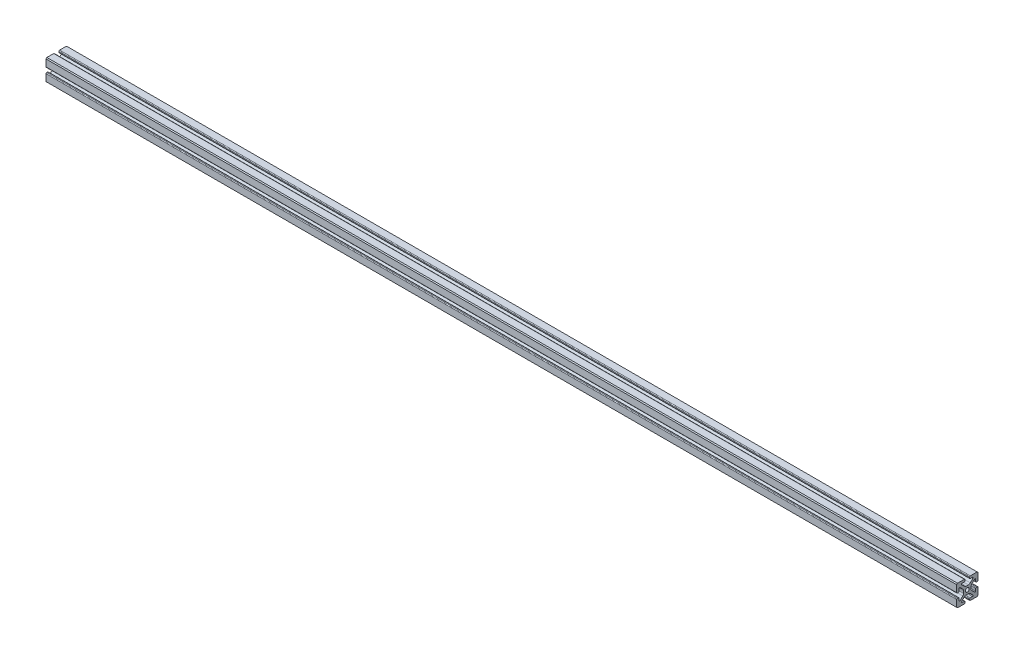
SolidWorks part; units mm, degrees
ref_plane "Front Plane" through (0, 0, 0) normal (0, 0, 1) x (1, 0, 0)
ref_plane "Top Plane" through (0, 0, 0) normal (0, 1, 0) x (1, 0, 0)
ref_plane "Right Plane" through (0, 0, 0) normal (1, 0, 0) x (0, 0, -1)
ref_plane "Plane1" through (0, 0, 0) normal (-1, 0, 0) x (0, -1, 0)
sketch "Sketch1" plane through (0, 0, 0) normal (-1, 0, 0) x (0, -1, 0)
  line L0 (19.05, 5.334) -> (19.05, 17.526)
  line L1 (19.05, 17.526) -> (17.526, 19.05)
  line L2 (17.526, 19.05) -> (5.334, 19.05)
  line L3 (4.064, 17.78) -> (4.064, 16.1266)
  line L4 (5.334, 14.8566) -> (9.0964, 14.8566)
  line L5 (10.287, 13.666) -> (10.287, 13.6538)
  line L6 (9.9383, 12.8119) -> (5.2776, 8.1513)
  line L7 (1.91, 6.7564) -> (-1.91, 6.7564)
  line L8 (-5.2776, 8.1513) -> (-9.9383, 12.8119)
  line L9 (-10.287, 13.6538) -> (-10.287, 13.666)
  line L10 (-9.0964, 14.8566) -> (-5.334, 14.8566)
  line L11 (-4.064, 16.1266) -> (-4.064, 17.78)
  line L12 (-5.334, 19.05) -> (-17.526, 19.05)
  line L13 (-17.526, 19.05) -> (-19.05, 17.526)
  line L14 (-19.05, 17.526) -> (-19.05, 5.334)
  line L15 (-17.78, 4.064) -> (-16.1266, 4.064)
  line L16 (-14.8566, 5.334) -> (-14.8566, 9.0964)
  line L17 (-13.666, 10.287) -> (-13.6538, 10.287)
  line L18 (-12.8119, 9.9383) -> (-8.1513, 5.2776)
  line L19 (-6.7564, 1.91) -> (-6.7564, -1.91)
  line L20 (-8.1513, -5.2776) -> (-12.8119, -9.9383)
  line L21 (-13.6538, -10.287) -> (-13.666, -10.287)
  line L22 (-14.8566, -9.0964) -> (-14.8566, -5.334)
  line L23 (-16.1266, -4.064) -> (-17.78, -4.064)
  line L24 (-19.05, -5.334) -> (-19.05, -17.526)
  line L25 (-19.05, -17.526) -> (-17.526, -19.05)
  line L26 (-17.526, -19.05) -> (-5.334, -19.05)
  line L27 (-4.064, -17.78) -> (-4.064, -16.1266)
  line L28 (-5.334, -14.8566) -> (-9.0964, -14.8566)
  line L29 (-10.287, -13.666) -> (-10.287, -13.6538)
  line L30 (-9.9383, -12.8119) -> (-5.2776, -8.1513)
  line L31 (-1.91, -6.7564) -> (1.91, -6.7564)
  line L32 (5.2776, -8.1513) -> (9.9383, -12.8119)
  line L33 (10.287, -13.6538) -> (10.287, -13.666)
  line L34 (9.0964, -14.8566) -> (5.334, -14.8566)
  line L35 (4.064, -16.1266) -> (4.064, -17.78)
  line L36 (5.334, -19.05) -> (17.526, -19.05)
  line L37 (17.526, -19.05) -> (19.05, -17.526)
  line L38 (19.05, -17.526) -> (19.05, -5.334)
  line L39 (17.78, -4.064) -> (16.1266, -4.064)
  line L40 (14.8566, -5.334) -> (14.8566, -9.0964)
  line L41 (13.666, -10.287) -> (13.6538, -10.287)
  line L42 (12.8119, -9.9383) -> (8.1513, -5.2776)
  line L43 (6.7564, -1.91) -> (6.7564, 1.91)
  line L44 (8.1513, 5.2776) -> (12.8119, 9.9383)
  line L45 (13.6538, 10.287) -> (13.666, 10.287)
  line L46 (14.8566, 9.0964) -> (14.8566, 5.334)
  line L47 (16.1266, 4.064) -> (17.78, 4.064)
  arc A0 (17.78, 4.064) -> (19.05, 5.334) centre (17.78, 5.334) ccw
  arc A1 (5.334, 19.05) -> (4.064, 17.78) centre (5.334, 17.78) ccw
  arc A2 (4.064, 16.1266) -> (5.334, 14.8566) centre (5.334, 16.1266) ccw
  arc A3 (9.0964, 14.8566) -> (10.287, 13.666) centre (9.0964, 13.666) cw
  arc A4 (10.287, 13.6538) -> (9.9383, 12.8119) centre (9.0964, 13.6538) cw
  arc A5 (5.2776, 8.1513) -> (1.91, 6.7564) centre (1.91, 11.5189) cw
  arc A6 (-1.91, 6.7564) -> (-5.2776, 8.1513) centre (-1.91, 11.5189) cw
  arc A7 (-9.9383, 12.8119) -> (-10.287, 13.6538) centre (-9.0964, 13.6538) cw
  arc A8 (-10.287, 13.666) -> (-9.0964, 14.8566) centre (-9.0964, 13.666) cw
  arc A9 (-5.334, 14.8566) -> (-4.064, 16.1266) centre (-5.334, 16.1266) ccw
  arc A10 (-4.064, 17.78) -> (-5.334, 19.05) centre (-5.334, 17.78) ccw
  arc A11 (-19.05, 5.334) -> (-17.78, 4.064) centre (-17.78, 5.334) ccw
  arc A12 (-16.1266, 4.064) -> (-14.8566, 5.334) centre (-16.1266, 5.334) ccw
  arc A13 (-14.8566, 9.0964) -> (-13.666, 10.287) centre (-13.666, 9.0964) cw
  arc A14 (-13.6538, 10.287) -> (-12.8119, 9.9383) centre (-13.6538, 9.0964) cw
  arc A15 (-8.1513, 5.2776) -> (-6.7564, 1.91) centre (-11.5189, 1.91) cw
  arc A16 (-6.7564, -1.91) -> (-8.1513, -5.2776) centre (-11.5189, -1.91) cw
  arc A17 (-12.8119, -9.9383) -> (-13.6538, -10.287) centre (-13.6538, -9.0964) cw
  arc A18 (-13.666, -10.287) -> (-14.8566, -9.0964) centre (-13.666, -9.0964) cw
  arc A19 (-14.8566, -5.334) -> (-16.1266, -4.064) centre (-16.1266, -5.334) ccw
  arc A20 (-17.78, -4.064) -> (-19.05, -5.334) centre (-17.78, -5.334) ccw
  arc A21 (-5.334, -19.05) -> (-4.064, -17.78) centre (-5.334, -17.78) ccw
  arc A22 (-4.064, -16.1266) -> (-5.334, -14.8566) centre (-5.334, -16.1266) ccw
  arc A23 (-9.0964, -14.8566) -> (-10.287, -13.666) centre (-9.0964, -13.666) cw
  arc A24 (-10.287, -13.6538) -> (-9.9383, -12.8119) centre (-9.0964, -13.6538) cw
  arc A25 (-5.2776, -8.1513) -> (-1.91, -6.7564) centre (-1.91, -11.5189) cw
  arc A26 (1.91, -6.7564) -> (5.2776, -8.1513) centre (1.91, -11.5189) cw
  arc A27 (9.9383, -12.8119) -> (10.287, -13.6538) centre (9.0964, -13.6538) cw
  arc A28 (10.287, -13.666) -> (9.0964, -14.8566) centre (9.0964, -13.666) cw
  arc A29 (5.334, -14.8566) -> (4.064, -16.1266) centre (5.334, -16.1266) ccw
  arc A30 (4.064, -17.78) -> (5.334, -19.05) centre (5.334, -17.78) ccw
  arc A31 (19.05, -5.334) -> (17.78, -4.064) centre (17.78, -5.334) ccw
  arc A32 (16.1266, -4.064) -> (14.8566, -5.334) centre (16.1266, -5.334) ccw
  arc A33 (14.8566, -9.0964) -> (13.666, -10.287) centre (13.666, -9.0964) cw
  arc A34 (13.6538, -10.287) -> (12.8119, -9.9383) centre (13.6538, -9.0964) cw
  arc A35 (8.1513, -5.2776) -> (6.7564, -1.91) centre (11.5189, -1.91) cw
  arc A36 (6.7564, 1.91) -> (8.1513, 5.2776) centre (11.5189, 1.91) cw
  arc A37 (12.8119, 9.9383) -> (13.6538, 10.287) centre (13.6538, 9.0964) cw
  arc A38 (13.666, 10.287) -> (14.8566, 9.0964) centre (13.666, 9.0964) cw
  arc A39 (14.8566, 5.334) -> (16.1266, 4.064) centre (16.1266, 5.334) ccw
  circle A40 centre (0, 0) radius 3.4036
extrude "Boss-Extrude1" add sketch "Sketch1" against normal blind 1625.6
